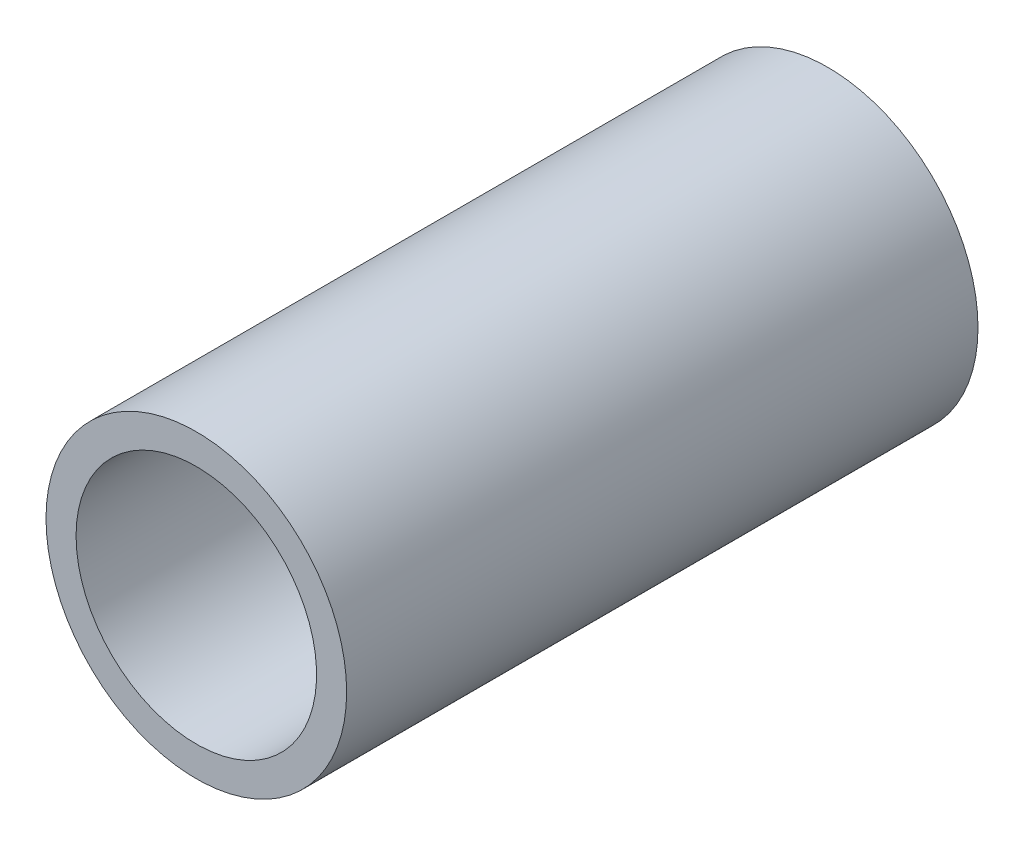
SolidWorks part; units mm, degrees
material "POM 乙缩醛共聚物"
ref_plane "前视基准面" through (0, 0, 0) normal (0, 0, 1) x (1, 0, 0)
ref_plane "上视基准面" through (0, 0, 0) normal (0, 1, 0) x (1, 0, 0)
ref_plane "右视基准面" through (0, 0, 0) normal (1, 0, 0) x (0, 0, -1)
sketch "草图1" plane through (0, 0, 0) normal (0, 0, 1) x (1, 0, 0)
  circle A0 centre (0, 0) radius 4
  circle A1 centre (0, 0) radius 5
  dimension "D1" = 8
  dimension "D2" = 10
extrude "凸台-拉伸1" add sketch "草图1" along normal blind 21
